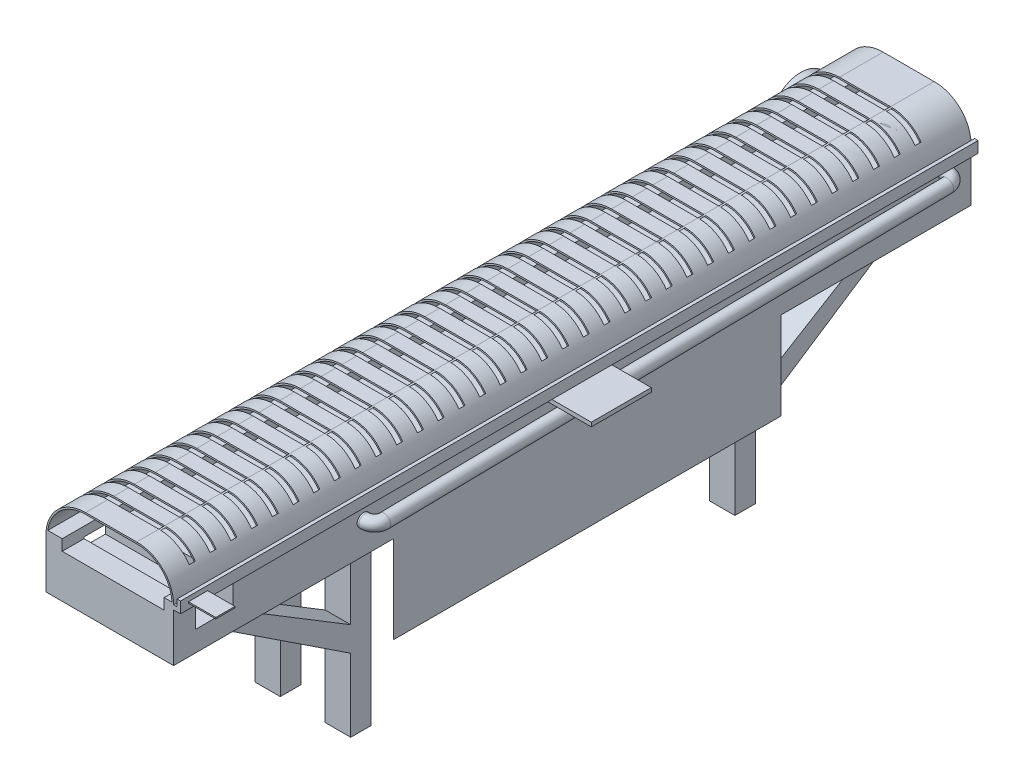
SolidWorks part; units mm, degrees
ref_plane "Alzado" through (0, 0, 0) normal (0, 0, 1) x (1, 0, 0)
ref_plane "Planta" through (0, 0, 0) normal (0, 1, 0) x (1, 0, 0)
ref_plane "Vista lateral" through (0, 0, 0) normal (1, 0, 0) x (0, 0, -1)
sketch "Croquis1" plane through (0, 0, 0) normal (0, 1, 0) x (1, 0, 0)
  line L1 (-400, 2500) -> (400, 2500)
  line L2 (-400, 2500) -> (-400, -2500)
  line L3 (-400, -2500) -> (400, -2500)
  line L4 (400, 2500) -> (400, -2500)
  line L5 (-400, 2500) -> (400, -2500) construction
  line L6 (-400, -2500) -> (400, 2500) construction
  point P0 (0, 0)
  dimension "D1" = 800
  dimension "D2" = 5000
extrude "Saliente-Extruir1" add sketch "Croquis1" along normal blind 330
sketch "Croquis2" plane through (0, 0, 2500) normal (0, 0, 1) x (1, 0, 0)
  line L0 (-400, 330) -> (400, 330)
  line L1 (168.0943, 555.5174) -> (-151.9057, 555.5174)
  line L2 (0, 0) -> (0, 555.5174) construction
  line L3 (-388.7435, 340) -> (389.768, 340)
  line L4 (168.2355, 545.5174) -> (-151.9057, 545.5174)
  arc A0 (400, 330) -> (168.0943, 555.5174) centre (174.3946, 330) ccw
  arc A1 (-151.9057, 555.5174) -> (-400, 330) centre (-151.9057, 306.293) ccw
  arc A2 (-151.9057, 545.5174) -> (-388.7435, 340) centre (-151.9057, 306.293) ccw
  arc A3 (389.768, 340) -> (168.2355, 545.5174) centre (174.3946, 330) ccw
  dimension "D1" = 320
  dimension "D2" = 10
extrude "Saliente-Extruir2" add sketch "Croquis2" against normal blind 5000
sketch "Croquis3" plane through (0, 555.5174, 0) normal (0, 1, 0) x (1, 0, 0)
  line L1 (359.6044, -2360.9572) -> (-359.6044, -2360.9572)
  line L2 (359.6044, -2360.9572) -> (359.6044, -2323.1785)
  line L3 (359.6044, -2323.1785) -> (-359.6044, -2323.1785)
  line L4 (-359.6044, -2360.9572) -> (-359.6044, -2323.1785)
  line L5 (359.6044, -2360.9572) -> (-359.6044, -2323.1785) construction
  line L6 (359.6044, -2323.1785) -> (-359.6044, -2360.9572) construction
  point P0 (108.2942, -2372.0617)
  point P1 (0, -2342.0679)
extrude "Cortar-Extruir2" cut sketch "Croquis3" against normal blind 127
pattern_linear "MatrizL1" count 36 spacing 130 along (0, 0, -1) of "Cortar-Extruir2"
sketch "Croquis4" plane through (0, 0, -2500) normal (0, 0, -1) x (-1, 0, 0)
  line L0 (-368.0797, 340) -> (-340.7132, 340)
  line L1 (388.7435, 340) -> (-389.768, 340) construction
  line L2 (-340.7132, 340) -> (-340.7132, 271.6452)
  line L3 (-340.7132, 271.6452) -> (298.2951, 271.6452)
  line L4 (298.2951, 271.6452) -> (298.2951, 340)
  line L5 (-340.7132, 340) -> (298.2951, 340)
  line M13 (388.7435, 340) -> (-389.768, 340)
extrude "Cortar-Extruir3" cut sketch "Croquis4" against normal blind 5133 contours L3 L4 L2 M13
sketch "Croquis5" plane through (400, 0, 0) normal (1, 0, 0) x (0, 0, -1)
  line L1 (-2363.3059, 281.3704) -> (-2127.6459, 281.3704)
  line L2 (-2363.3059, 281.3704) -> (-2363.3059, 128.1914)
  line L3 (-2363.3059, 128.1914) -> (-2127.6459, 128.1914)
  line L4 (-2127.6459, 281.3704) -> (-2127.6459, 128.1914)
  line L5 (-2363.3059, 281.3704) -> (-2127.6459, 128.1914) construction
  line L6 (-2363.3059, 128.1914) -> (-2127.6459, 281.3704) construction
  point P0 (-2245.4759, 204.7809)
extrude "Cortar-Extruir4" cut sketch "Croquis5" against normal blind 5133
sketch "Croquis6" plane through (400, 0, 0) normal (1, 0, 0) x (0, 0, -1)
  circle A0 centre (-1309.1477, 195.6714) radius 40.3235
sketch3d "Croquis3D1"
  line L0 (400, 195.6714, 1309.1477) -> (410.4472, 195.6714, 1309.1477)
  line L1 (470.4472, 196.6352, 1249.1555) -> (470.4472, 253.3191, -2279.3911)
  line L2 (410.4472, 254.2828, -2339.3834) -> (380.8779, 254.2828, -2339.3834)
  arc A0 (410.4472, 195.6714, 1309.1477) -> (470.4472, 196.6352, 1249.1555) centre (410.4472, 196.6352, 1249.1555) ccw
  arc A1 (470.4472, 253.3191, -2279.3911) -> (410.4472, 254.2828, -2339.3834) centre (410.4472, 253.3191, -2279.3911) ccw
  point P7 (470.4472, 195.6714, 1309.1477)
  point P8 (410.4472, 256.6274, 1250.1192)
  point P11 (470.4472, 254.2828, -2339.3834)
  point P12 (410.4472, 313.3113, -2278.4274)
  dimension "D1" = 60
sweep "Barrer1" add profiles "Croquis6" path "Croquis3D1"
ref_plane "Plano1" through (0, 0, 0) normal (1, 0, 0) x (0, 0, -1)
sketch "Croquis8" plane through (0, 0, 0) normal (1, 0, 0) x (0, 0, -1)
  line L0 (-20.9572, 555.5174) -> (-20.9572, -1044.4826) construction
  line L1 (-2181.8022, 0) -> (-1289.5305, -588.0371)
  line L2 (-2500, 0) -> (2500, 0) construction
  line L3 (-1289.5305, -433.0371) -> (-1289.5305, 0)
  line L4 (-1289.5305, 0) -> (-1289.5305, -433.0371)
  line L5 (-1289.5305, -1044.4826) -> (-1160.9829, -1044.4826)
  line L6 (-1160.9829, -1044.4826) -> (-1160.9829, 0)
  line L7 (-2001.8022, 0) -> (-1289.5305, -433.0371)
  line L8 (-2181.8022, 0) -> (-2001.8022, 0)
  line L9 (-1289.5305, 0) -> (-1160.9829, 0)
  line L10 (-1289.5305, -588.0371) -> (-1289.5305, -1044.4826)
  line L11 (1247.6161, -588.0371) -> (1247.6161, -1044.4826)
  line L12 (1247.6161, 0) -> (1119.0685, 0)
  line L13 (2139.8878, 0) -> (1959.8878, 0)
  line L14 (1959.8878, 0) -> (1247.6161, -433.0371)
  line L15 (1119.0685, -1044.4826) -> (1119.0685, 0)
  line L16 (1247.6161, -1044.4826) -> (1119.0685, -1044.4826)
  line L17 (1247.6161, 0) -> (1247.6161, -433.0371)
  line L18 (1247.6161, -433.0371) -> (1247.6161, 0)
  line L19 (2139.8878, 0) -> (1247.6161, -588.0371)
  dimension "D1" = 1600
  dimension "D2" = 180
  dimension "D3" = 155
extrude "Saliente-Extruir3" add sketch "Croquis8" along normal blind 300 and the other way blind 300 contours L19 L13 L14 L17 L12 L15 L16 L11 | L1 L10 L5 L6 L9 L3 L7 L8
sketch "Croquis9" plane through (0, 0, 2500) normal (0, 0, 1) x (1, 0, 0)
  line L0 (-141.5868, 0) -> (-141.5868, -1301.5991)
  line L1 (-300, 0) -> (300, 0) construction
  line L2 (-141.5868, -1301.5991) -> (140.1369, -1301.5991)
  line L3 (140.1369, -1301.5991) -> (140.1369, 0)
  line L4 (140.1369, 0) -> (-141.5868, 0)
extrude "Cortar-Extruir5" cut sketch "Croquis9" against normal blind 5271
sketch "Croquis10" plane through (-400, 0, 0) normal (-1, 0, 0) x (0, 0, 1)
  line L0 (-2186.2398, 287.9143) -> (-1603.752, -400.9762)
  line L1 (-1894.9959, -617.8344) -> (-2474.4333, 39.0055)
  arc A0 (-2186.2398, 287.9143) -> (-2474.4333, 39.0055) centre (-2331.6414, 164.9707) ccw
  arc A1 (-1603.752, -400.9762) -> (-1894.9959, -617.8344) centre (-1742.6568, -518.4265) cw
extrude "Saliente-Extruir5" add sketch "Croquis10" along normal blind 100
sketch "Croquis11" plane through (400, 0, 0) normal (1, 0, 0) x (0, 0, -1)
  line L0 (2139.8878, 0) -> (1247.6161, -588.0371) construction
  line L1 (-1120.1377, 84.2408) -> (1307.2126, 84.2408)
  line L2 (-1120.1377, 84.2408) -> (-1120.1377, -548.7609)
  line L3 (-1120.1377, -548.7609) -> (1307.2126, -548.7609)
  line L4 (1307.2126, 84.2408) -> (1307.2126, -548.7609)
  line L5 (-1120.1377, 84.2408) -> (1307.2126, -548.7609) construction
  line L6 (-1120.1377, -548.7609) -> (1307.2126, 84.2408) construction
  point P0 (93.5375, -232.2601)
extrude "Saliente-Extruir6" add sketch "Croquis11" against normal blind 1
sketch "Croquis12" plane through (0, 0, -2500) normal (0, 0, -1) x (-1, 0, 0)
  line L0 (-400, 302.6417) -> (-443.2755, 302.6417)
  line L1 (-400, 330) -> (-400, 0) construction
  line L2 (-443.2755, 302.6417) -> (-443.2755, 372.6998)
  line L3 (-443.2755, 372.6998) -> (-421.6378, 372.6998)
  line L4 (-421.6378, 372.6998) -> (-421.6378, 330)
  line L5 (-421.6378, 330) -> (-400, 330)
  line L6 (-400, 330) -> (-400, 302.6417)
extrude "Saliente-Extruir7" add sketch "Croquis12" against normal blind 5000
sketch "Croquis13" plane through (443.2755, 0, 0) normal (1, 0, 0) x (0, 0, -1)
  line L1 (-2450.0834, 343.8256) -> (-2329.7725, 343.8256)
  line L2 (-2450.0834, 343.8256) -> (-2450.0834, 335.6694)
  line L3 (-2450.0834, 335.6694) -> (-2329.7725, 335.6694)
  line L4 (-2329.7725, 343.8256) -> (-2329.7725, 335.6694)
  line L5 (-2450.0834, 343.8256) -> (-2329.7725, 335.6694) construction
  line L6 (-2450.0834, 335.6694) -> (-2329.7725, 343.8256) construction
  point P0 (-2389.928, 339.7475)
extrude "Saliente-Extruir8" add sketch "Croquis13" along normal blind 171
sketch "Croquis14" plane through (400, 0, 0) normal (1, 0, 0) x (0, 0, -1)
  line L0 (-164.0618, 295.2335) -> (211.965, 295.2335)
  line L1 (211.965, 295.2335) -> (211.965, 269.8928)
  line L2 (211.965, 269.8928) -> (-164.0618, 269.8928)
  line L3 (-164.0618, 269.8928) -> (-164.0618, 295.2335)
extrude "Saliente-Extruir9" add sketch "Croquis14" along normal blind 283
